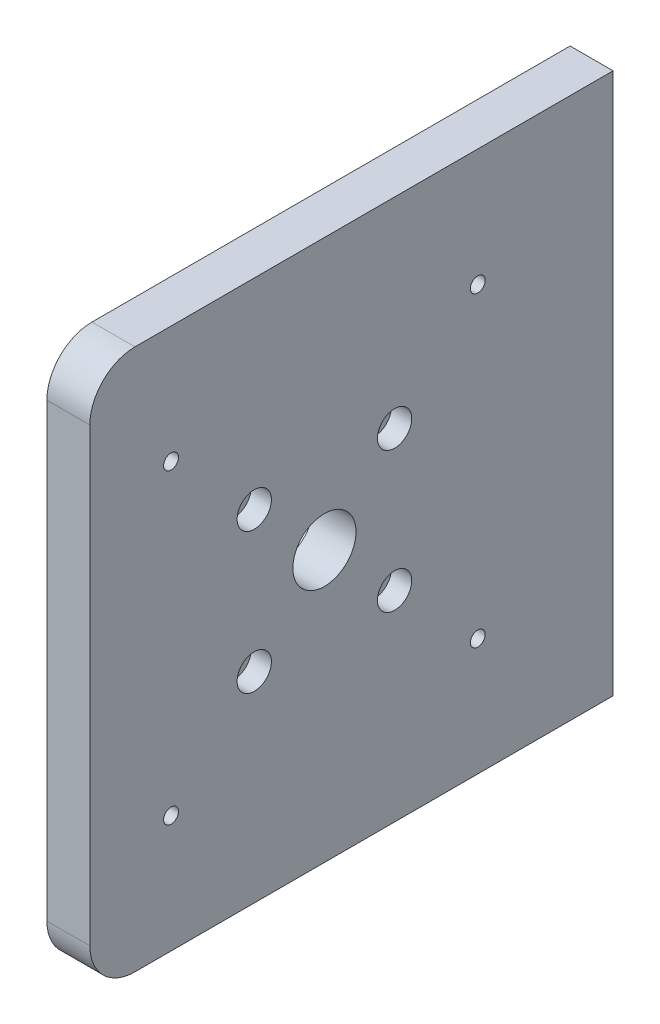
SolidWorks part; units mm, degrees
ref_plane "Front Plane" through (0, 0, 0) normal (1, 0, 0) x (0, 1, 0)
ref_plane "Top Plane" through (0, 0, 0) normal (0, 0, 1) x (0, 1, 0)
ref_plane "Right Plane" through (0, 0, 0) normal (0, 1, 0) x (-1, 0, 0)
sketch "Sketch1" plane through (0, 0, 0) normal (1, 0, 0) x (0, 1, 0)
  line L1 (-60, -58) -> (60, -58)
  line L2 (-60, -58) -> (-60, 58)
  line L3 (-60, 58) -> (60, 58)
  line L4 (60, -58) -> (60, 58)
  line L5 (-60, -58) -> (60, 58) construction
  line L6 (-60, 58) -> (60, -58) construction
  line L7 (0, 0) -> (-60, 0) construction
  point P0 (0, 0)
  dimension "D1" = 120
  dimension "D2" = 116
extrude "Boss-Extrude1" add sketch "Sketch1" along normal blind 9.525
sketch "Sketch2" plane through (9.525, 0, 0) normal (1, 0, 0) x (0, 1, 0)
  line L0 (0, 6) -> (-15.5563, 21.5563) construction
  line L1 (0, 6) -> (-7, 6) construction
  line L2 (-60, -58) -> (60, -58) construction
  circle A0 centre (0, 6) radius 7
  circle A1 centre (-15.5563, 21.5563) radius 2.1
  circle A2 centre (15.5563, 21.5563) radius 2.1
  circle A3 centre (15.5563, -9.5563) radius 2.1
  circle A4 centre (-15.5563, -9.5563) radius 2.1
  point P4 (7.1854, 17.2932)
  point P6 (0, 0)
  dimension "D1" = 14
  dimension "D2" = 4.2
  dimension "D3" = 45
  dimension "D4" = 22
  dimension "D6" = 64
  dimension "D5" = 4
hole_wizard "CBORE for M4 Hex Head Cap Screw1" positions "3DSketch2" profile "Sketch4" counterbore size "M4" standard "ISO" end condition through all
sketch3d "3DSketch2"
  point P0 (9.525, -15.5563, 21.5563)
  point P3 (9.525, 15.5563, 21.5563)
  point P6 (9.525, 15.5563, -9.5563)
  point P9 (9.525, -15.5563, -9.5563)
sketch "Sketch4" plane through (9.525, -15.5563, 21.5563) normal (0, 1, 0) x (0, 0, -1)
  line L0 (0, 0) -> (0, 9.525)
  line L1 (0, 9.525) -> (2.1, 9.525)
  line L3 (2.1, 9.525) -> (2.1, 4.5)
  line L4 (2.1, 4.5) -> (3.8, 4.5)
  line L5 (3.8, 4.5) -> (3.8, 0)
  line L7 (3.8, 0) -> (0, 0)
  line L11 (0, -6.35) -> (0, 107.95) construction
  dimension "Thru Hole Dia." = 4.2
  dimension "Thru Hole Depth" = 9.525
  dimension "C'Bore Dia." = 7.6
  dimension "C'Bore Depth" = 4.5
extrude "Cut-Extrude1" cut sketch "Sketch2" against normal through all contours A0
sketch "Sketch5" plane through (0, 0, -58) normal (0, 0, -1) x (1, 0, 0)
  line L0 (4.7625, 54) -> (4.7625, -54) construction
  line L1 (0, 0) -> (4.7625, 0) construction
  line L2 (9.525, 60) -> (0, 60) construction
  circle A0 centre (4.7625, 54) radius 1.65
  circle A1 centre (4.7625, 27) radius 1.65
  circle A2 centre (4.7625, 0) radius 1.65
  circle A3 centre (4.7625, -27) radius 1.65
  circle A4 centre (4.7625, -54) radius 1.65
  point P6 (4.7625, 30.9085)
  point P9 (4.7625, 60)
  dimension "D2" = 3.3
  dimension "D3" = 5
  dimension "D1" = 108
  dimension "D4" = 27
extrude "Cut-Extrude2" cut sketch "Sketch5" against normal blind 10 contours A1 | A2 | A3 | A4 | A0
sketch "Sketch6" plane through (9.525, 0, 0) normal (1, 0, 0) x (0, 1, 0)
  line L1 (-34, -28) -> (34, -28) construction
  line L2 (-34, -28) -> (-34, 40) construction
  line L3 (-34, 40) -> (34, 40) construction
  line L4 (34, -28) -> (34, 40) construction
  line L5 (-34, -28) -> (34, 40) construction
  line L6 (-34, 40) -> (34, -28) construction
  circle A0 centre (0, 6) radius 7 construction
  circle A1 centre (0, 6) radius 7 construction
  circle A2 centre (-34, 40) radius 1.65
  circle A3 centre (34, 40) radius 1.65
  circle A4 centre (34, -28) radius 1.65
  circle A5 centre (-34, -28) radius 1.65
  point P9 (0, 6)
  dimension "D3" = 3.3
  dimension "D1" = 68
  dimension "D2" = 68
  dimension "D4" = 4
extrude "Cut-Extrude3" cut sketch "Sketch6" against normal through all contours A3 | A4 | A5 | A2
fillet "Fillet1" radius 10 2 edges at (4.7625, -60, 58) (4.7625, 60, 58)
